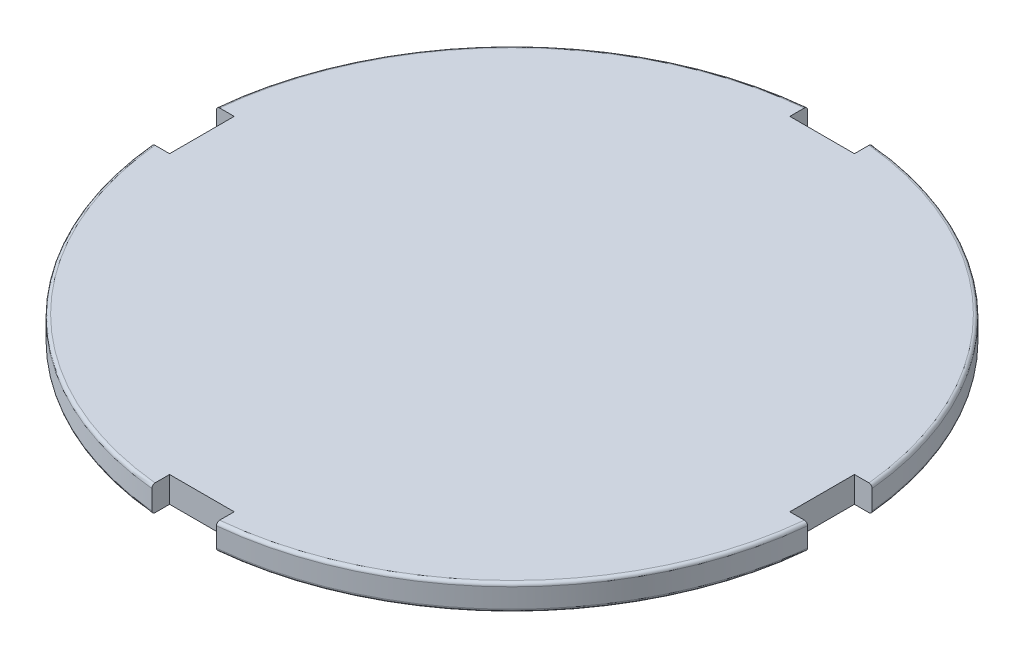
SolidWorks part; units mm, degrees
ref_plane "Front" through (0, 0, 0) normal (0, 0, 1) x (1, 0, 0)
ref_plane "Top" through (0, 0, 0) normal (0, 1, 0) x (1, 0, 0)
ref_plane "Right" through (0, 0, 0) normal (1, 0, 0) x (0, 0, -1)
sketch "Sketch2" plane through (0, 0, 0) normal (0, 1, 0) x (1, 0, 0)
  circle A0 centre (0, 0) radius 64.77
  dimension "D1" = 129.54
extrude "Boss-Extrude1" add sketch "Sketch2" along normal blind 5.08
fillet "Fillet1" radius 0.635 2 edges at (0, 0, 64.77) (0, 5.08, 64.77)
sketch "Sketch3" plane through (0, 0, 0) normal (0, -1, 0) x (1, 0, 0)
  line L0 (75.9093, 0) -> (-75.3573, 0) construction
  line L1 (0, -77.1055) -> (0, 79.4978) construction
  line L2 (13.8937, 0) -> (13.8937, 60.96) construction
  line L3 (-6.35, 76.1854) -> (6.35, 76.1854)
  line L4 (6.35, 76.1854) -> (6.35, 60.96)
  line L5 (6.35, 60.96) -> (-6.35, 60.96)
  line L6 (-6.35, 60.96) -> (-6.35, 76.1854)
  line L7 (60.96, 6.35) -> (76.1854, 6.35)
  line L8 (76.1854, 6.35) -> (76.1854, -6.35)
  line L9 (76.1854, -6.35) -> (60.96, -6.35)
  line L10 (60.96, -6.35) -> (60.96, 6.35)
  line L11 (6.35, -60.96) -> (6.35, -76.1854)
  line L12 (6.35, -76.1854) -> (-6.35, -76.1854)
  line L13 (-6.35, -76.1854) -> (-6.35, -60.96)
  line L14 (-6.35, -60.96) -> (6.35, -60.96)
  line L15 (-60.96, -6.35) -> (-76.1854, -6.35)
  line L16 (-76.1854, -6.35) -> (-76.1854, 6.35)
  line L17 (-76.1854, 6.35) -> (-60.96, 6.35)
  line L18 (-60.96, 6.35) -> (-60.96, -6.35)
  point P10 (0, 76.1854)
  point P27 (0, 0)
  dimension "D1" = 60.96
  dimension "D2" = 6.35
  dimension "D3" = 4
extrude "Cut-Extrude1" cut sketch "Sketch3" against normal through all
